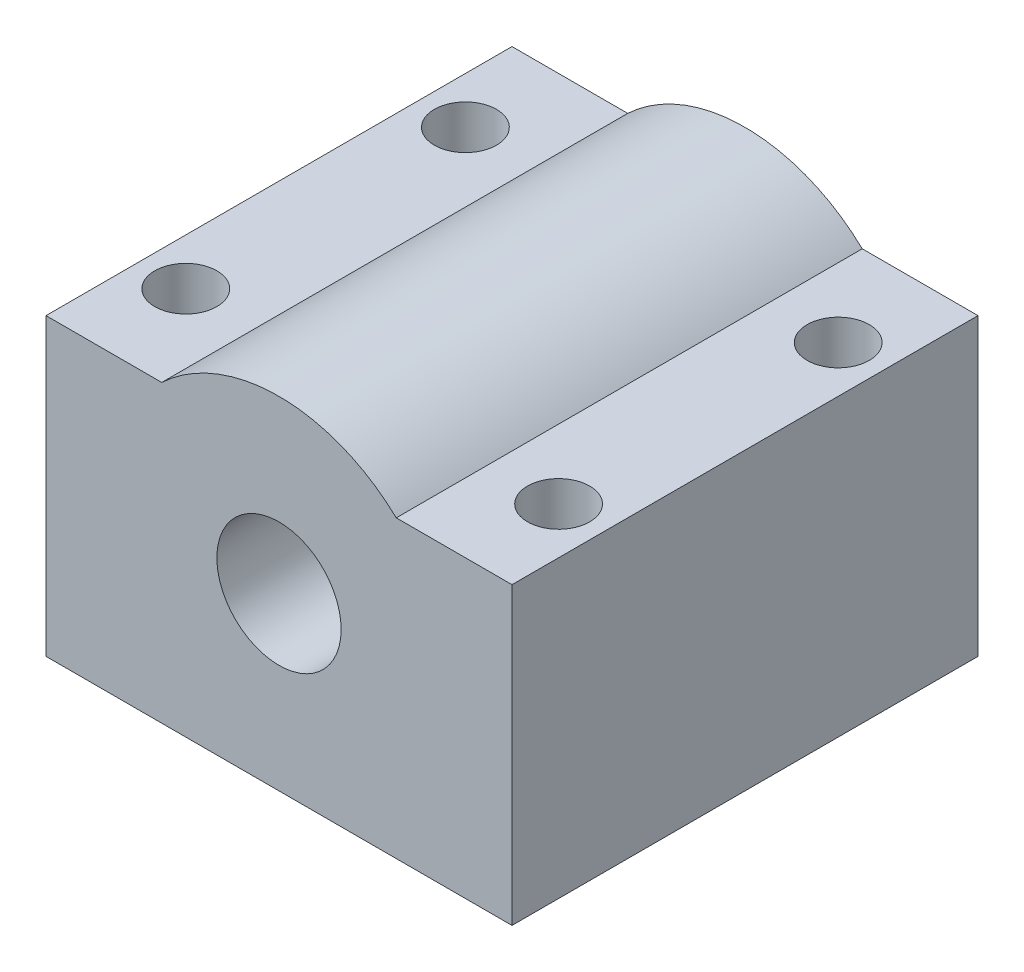
SolidWorks part; units mm, degrees
ref_plane "Płaszczyzna przednia" through (0, 0, 0) normal (0, 0, 1) x (1, 0, 0)
ref_plane "Płaszczyzna górna" through (0, 0, 0) normal (0, 1, 0) x (1, 0, 0)
ref_plane "Płaszczyzna prawa" through (0, 0, 0) normal (1, 0, 0) x (0, 0, -1)
sketch "Szkic1" plane through (0, 0, 0) normal (0, 0, 1) x (1, 0, 0)
  circle A0 centre (0, 0) radius 4
  circle A1 centre (0, 0) radius 11
  point P4 (0, 0)
extrude "Dodanie-wyciągnięcie1" add sketch "Szkic1" along normal blind 30
sketch "Szkic5" plane through (0, 0, 0) normal (0, 0, -1) x (-1, 0, 0)
  line L1 (0, -11) -> (15, -11)
  line L2 (0, -11) -> (0, -4)
  line L3 (0, -4) -> (15, -4)
  line L4 (15, -11) -> (15, -4)
  circle A0 centre (0, 0) radius 11 construction
  point P6 (0, 0)
extrude "Dodanie-wyciągnięcie2" add sketch "Szkic5" against normal blind 30
sketch "Szkic6" plane through (0, 0, 0) normal (0, 0, 1) x (1, 0, 0)
  line L1 (0, -11) -> (15, -11)
  line L2 (0, -11) -> (0, -4)
  line L3 (0, -4) -> (15, -4)
  line L4 (15, -11) -> (15, -4)
extrude "Dodanie-wyciągnięcie3" add sketch "Szkic6" along normal blind 30
sketch "Szkic7" plane through (0, 0, 0) normal (0, 0, 1) x (1, 0, 0)
  line L1 (15, -4) -> (7.5498, -4)
  line L2 (15, -4) -> (15, 8)
  line L3 (15, 8) -> (7.5498, 8)
  line L4 (7.5498, -4) -> (7.5498, 8)
  line L5 (-15, -4) -> (-7.5498, -4)
  line L6 (-15, -4) -> (-15, 8)
  line L7 (-15, 8) -> (-7.5498, 8)
  line L8 (-7.5498, -4) -> (-7.5498, 8)
  arc A0 (10.247, -4) -> (-10.247, -4) centre (0, 0) ccw construction
extrude "Dodanie-wyciągnięcie4" add sketch "Szkic7" along normal blind 30
sketch "Szkic8" plane through (0, -11, 0) normal (0, -1, 0) x (1, 0, 0)
  circle A0 centre (-12, 24) radius 2
  circle A1 centre (12, 24) radius 2
  circle A2 centre (12, 6) radius 2
  circle A3 centre (-12, 6) radius 2
  dimension "D1" = 4
extrude "Wytnij-wyciągnięcie1" cut sketch "Szkic8" against normal up to next
